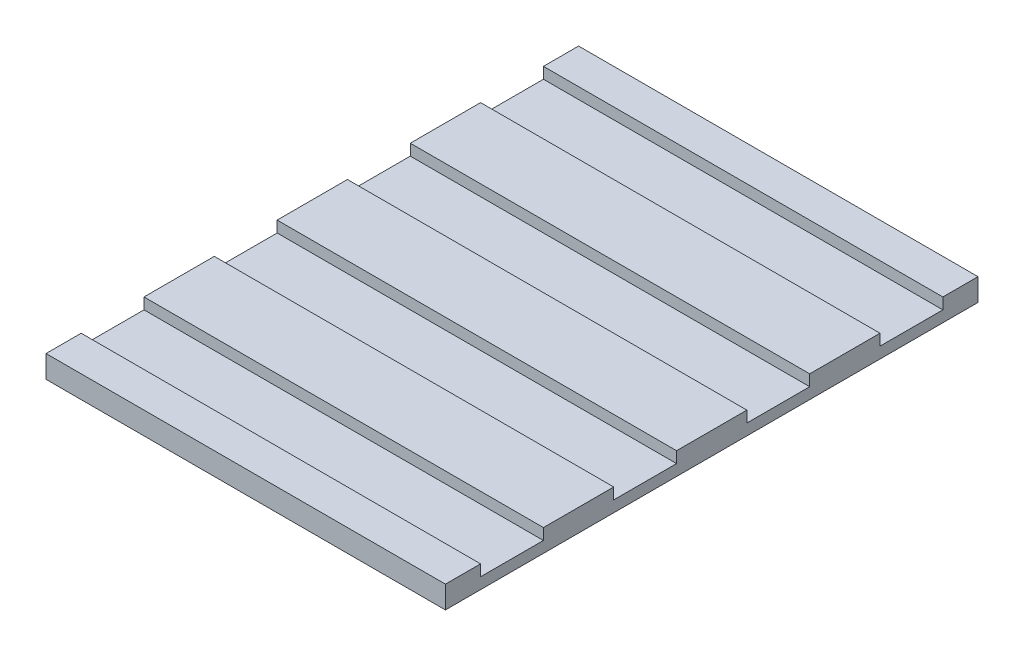
SolidWorks part; units mm, degrees
ref_plane "Front Plane" through (0, 0, 0) normal (0, 0, 1) x (1, 0, 0)
ref_plane "Top Plane" through (0, 0, 0) normal (0, 1, 0) x (1, 0, 0)
ref_plane "Right Plane" through (0, 0, 0) normal (1, 0, 0) x (0, 0, -1)
sketch "Sketch1" plane through (0, 0, 0) normal (0, 1, 0) x (1, 0, 0)
  line L1 (-10.8333, 95.6713) -> (64.1667, 95.6713)
  line L2 (-10.8333, 95.6713) -> (-10.8333, -4.3287)
  line L3 (-10.8333, -4.3287) -> (64.1667, -4.3287)
  line L4 (64.1667, 95.6713) -> (64.1667, -4.3287)
  dimension "D1" = 100
  dimension "D2" = 75
extrude "Boss-Extrude2" add sketch "Sketch1" along normal blind 4.2
sketch "Sketch4" plane through (0, 4.2, 0) normal (0, 1, 0) x (1, 0, 0)
  line L0 (-10.8333, -4.3287) -> (64.1667, -4.3287) construction
  line L1 (64.1667, -4.3287) -> (64.1667, 95.6713) construction
  line L2 (64.1667, 95.6713) -> (-10.8333, 95.6713) construction
  line L3 (-10.8333, 89.0713) -> (64.1667, 89.0713)
  line L4 (-10.8333, 89.0713) -> (-10.8333, 77.2713)
  line L5 (-10.8333, 77.2713) -> (64.1667, 77.2713)
  line L6 (64.1667, 89.0713) -> (64.1667, 77.2713)
  line L7 (-10.8333, 89.0713) -> (64.1667, 77.2713) construction
  line L8 (-10.8333, 77.2713) -> (64.1667, 89.0713) construction
  line L9 (-10.8333, 95.6713) -> (-10.8333, -4.3287) construction
  line L10 (-10.8333, 64.0713) -> (64.1667, 64.0713)
  line L11 (-10.8333, 64.0713) -> (-10.8333, 52.2713)
  line L12 (-10.8333, 52.2713) -> (64.1667, 52.2713)
  line L13 (64.1667, 64.0713) -> (64.1667, 52.2713)
  line L14 (-10.8333, 64.0713) -> (64.1667, 52.2713) construction
  line L15 (-10.8333, 52.2713) -> (64.1667, 64.0713) construction
  line L16 (-10.8333, 39.0713) -> (64.1667, 39.0713)
  line L17 (-10.8333, 39.0713) -> (-10.8333, 27.2713)
  line L18 (-10.8333, 27.2713) -> (64.1667, 27.2713)
  line L19 (64.1667, 39.0713) -> (64.1667, 27.2713)
  line L20 (-10.8333, 39.0713) -> (64.1667, 27.2713) construction
  line L21 (-10.8333, 27.2713) -> (64.1667, 39.0713) construction
  line L22 (-10.8333, 14.0713) -> (64.1667, 14.0713)
  line L23 (-10.8333, 14.0713) -> (-10.8333, 2.2713)
  line L24 (-10.8333, 2.2713) -> (64.1667, 2.2713)
  line L25 (64.1667, 14.0713) -> (64.1667, 2.2713)
  line L26 (-10.8333, 14.0713) -> (64.1667, 2.2713) construction
  line L27 (-10.8333, 2.2713) -> (64.1667, 14.0713) construction
  point P0 (26.6667, -4.3287)
  point P1 (26.6667, 83.1713)
  point P6 (46.1167, 45.6713)
  point P8 (46.1167, 70.6713)
  point P10 (26.6667, 95.6713)
  point P11 (46.1167, 20.6713)
  point P15 (0, 0)
  point P17 (26.6667, 83.1713)
  point P20 (26.6667, 58.1713)
  point P25 (26.6667, 33.1713)
  point P30 (26.6667, 8.1713)
  point P37 (0, 0)
  dimension "D1" = 11.8
  dimension "D2" = 11.8
  dimension "D3" = 11.8
  dimension "D4" = 11.8
  dimension "D5" = 0
  dimension "D6" = 0
  dimension "D7" = 0
  dimension "D8" = 0
  dimension "D9" = 0
extrude "Cut-Extrude2" cut sketch "Sketch4" against normal blind 2.1
